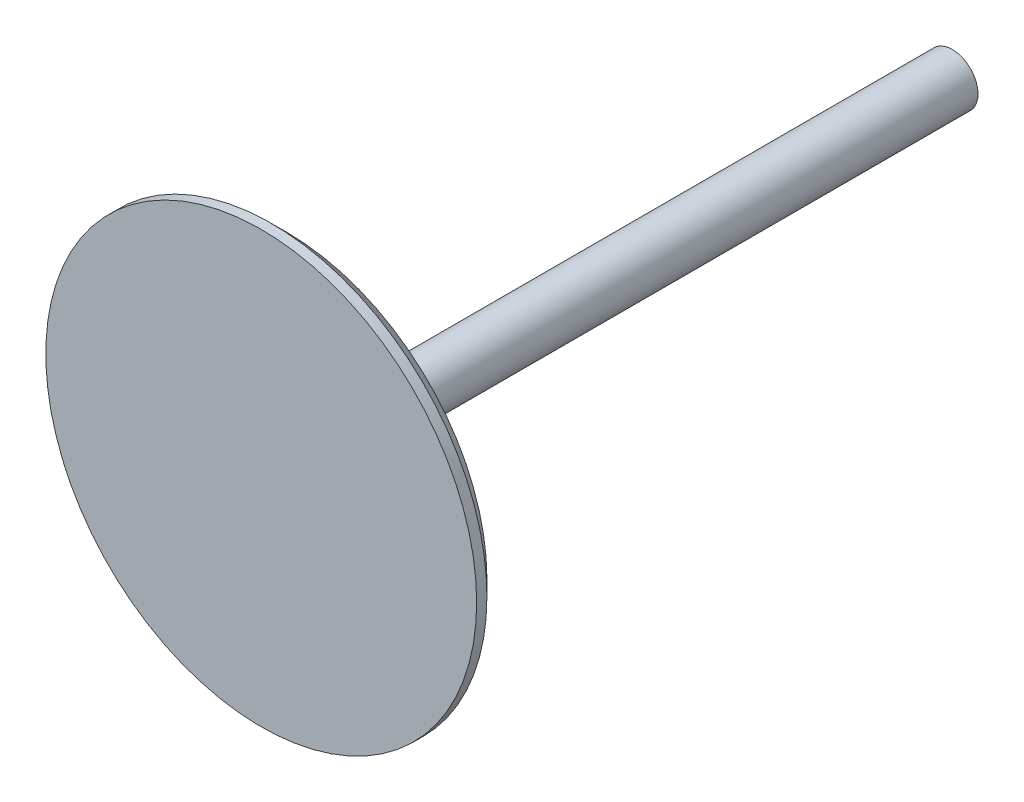
SolidWorks part; units mm, degrees
ref_plane "Front Plane" through (0, 0, 0) normal (0, 0, 1) x (1, 0, 0)
ref_plane "Top Plane" through (0, 0, 0) normal (0, 1, 0) x (1, 0, 0)
ref_plane "Right Plane" through (0, 0, 0) normal (1, 0, 0) x (0, 0, -1)
sketch "Sketch1" plane through (0, 0, 0) normal (0, 1, 0) x (1, 0, 0)
  line L0 (0, 0) -> (0, 85.55)
  line L1 (0, 85.55) -> (3.18, 85.55)
  line L2 (3.18, 85.55) -> (3.18, 17.0542)
  line L3 (24.76, 3.18) -> (26.67, 1.27)
  line L4 (26.67, 1.27) -> (26.67, 0)
  line L5 (26.67, 0) -> (0, 0)
  arc A0 (3.18, 17.0542) -> (24.76, 3.18) centre (18.43, 17.0542) ccw
  dimension "D7" = 15.25
  dimension "D1" = 85.55
  dimension "D2" = 26.67
  dimension "D3" = 3.18
  dimension "D4" = 1.27
  dimension "D5" = 3.18
  dimension "D6" = 45
revolve "Revolve1" add sketch "Sketch1" angle 360 about L0
